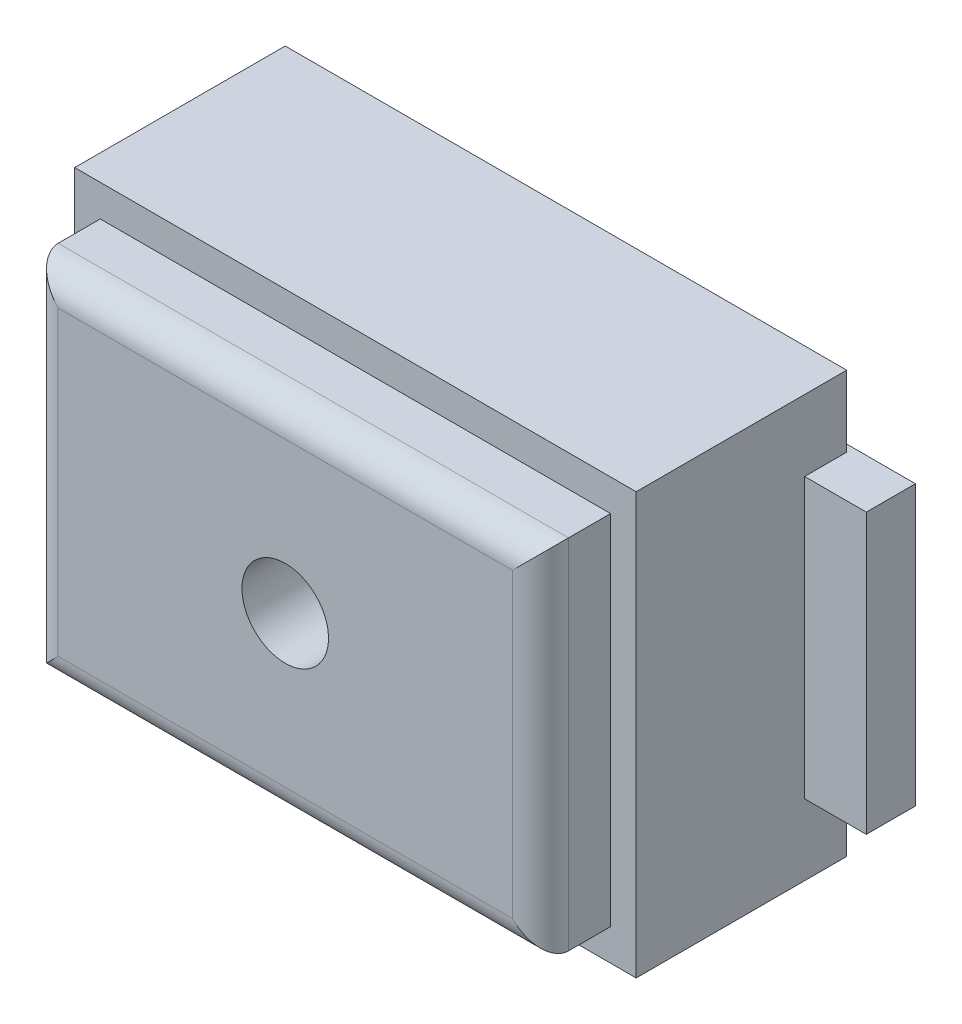
SolidWorks part; units mm, degrees
ref_plane "前视基准面" through (0, 0, 0) normal (0, 0, 1) x (1, 0, 0)
ref_plane "上视基准面" through (0, 0, 0) normal (0, 1, 0) x (1, 0, 0)
ref_plane "右视基准面" through (0, 0, 0) normal (1, 0, 0) x (0, 0, -1)
sketch "草图1" plane through (0, 0, 0) normal (0, 0, 1) x (1, 0, 0)
  line L1 (2, -1.5) -> (-2, -1.5)
  line L2 (2, -1.5) -> (2, 1.5)
  line L3 (2, 1.5) -> (-2, 1.5)
  line L4 (-2, -1.5) -> (-2, 1.5)
  line L5 (2, -1.5) -> (-2, 1.5) construction
  line L6 (2, 1.5) -> (-2, -1.5) construction
  point P0 (0, 0)
extrude "凸台-拉伸1" add sketch "草图1" along normal blind 1.5
sketch "草图2" plane through (0, 0, 0) normal (0, 0, 1) x (1, 0, 0)
  line L1 (1.8177, -1.2742) -> (-1.8177, -1.2742)
  line L2 (1.8177, -1.2742) -> (1.8177, 1.2742)
  line L3 (1.8177, 1.2742) -> (-1.8177, 1.2742)
  line L4 (-1.8177, -1.2742) -> (-1.8177, 1.2742)
  line L5 (1.8177, -1.2742) -> (-1.8177, 1.2742) construction
  line L6 (1.8177, 1.2742) -> (-1.8177, -1.2742) construction
  point P0 (0, 0)
extrude "凸台-拉伸2" add sketch "草图2" along normal blind 0.5 from surface at 1.5 starting at face at (0, 0, 1.5)
fillet "圆角1" radius 0.2 4 edges at (1.8177, 0, 2) (0, -1.2742, 2) (-1.8177, 0, 2) (0, 1.2742, 2)
sketch "草图3" plane through (0, 0, 0) normal (0, 0, 1) x (1, 0, 0)
  circle A0 centre (0, 0) radius 0.3083
extrude "切除-拉伸1" cut sketch "草图3" against normal blind 0.5 from surface at 2 starting at face at (0, 0, 2)
sketch "草图4" plane through (0, 0, 0) normal (0, 0, 1) x (1, 0, 0)
  line L0 (2, -1.5) -> (2, 1.5) construction
  line L1 (-2.4506, -0.9942) -> (-1.5827, -0.9942)
  line L2 (1.5604, -0.9942) -> (2.4396, -0.9942)
  line L3 (1.5604, -0.9942) -> (1.5604, 0.9942)
  line L4 (1.5604, 0.9942) -> (2.4396, 0.9942)
  line L5 (2.4396, -0.9942) -> (2.4396, 0.9942)
  line L6 (1.5604, -0.9942) -> (2.4396, 0.9942) construction
  line L7 (1.5604, 0.9942) -> (2.4396, -0.9942) construction
  line L8 (-2.4506, -0.9942) -> (-2.4506, 0.9942)
  line L9 (-2.4506, 0.9942) -> (-1.5827, 0.9942)
  line L10 (-1.5827, -0.9942) -> (-1.5827, 0.9942)
  line L11 (-2.4506, -0.9942) -> (-1.5827, 0.9942) construction
  line L12 (-2.4506, 0.9942) -> (-1.5827, -0.9942) construction
  point P2 (2, 0)
  point P7 (-2.0166, 0)
extrude "凸台-拉伸3" add sketch "草图4" along normal blind 0.3 and the other way blind 0.05
